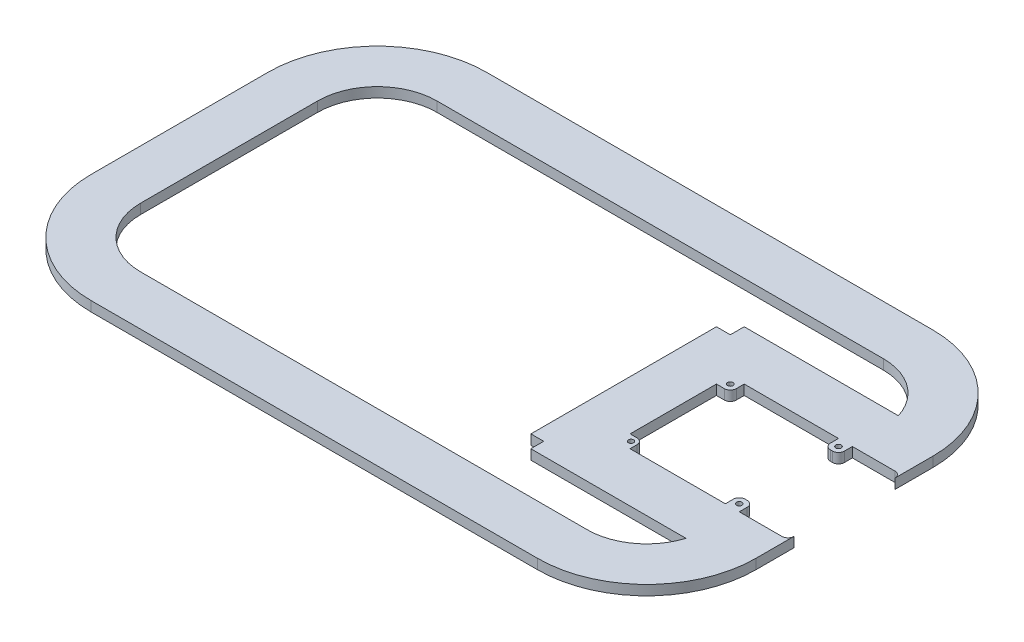
SolidWorks part; units mm, degrees
ref_plane "Front Plane" through (0, 0, 0) normal (0, 0, 1) x (1, 0, 0)
ref_plane "Top Plane" through (0, 0, 0) normal (0, 1, 0) x (1, 0, 0)
ref_plane "Right Plane" through (0, 0, 0) normal (1, 0, 0) x (0, 0, -1)
sketch "Sketch1" plane through (0, 0, 0) normal (0, 1, 0) x (1, 0, 0)
  line L0 (279.931, -90.3676) -> (279.931, -109.4976)
  line L1 (-0.099, 34.7624) -> (224.931, 34.7624)
  line L2 (-55.099, -20.2376) -> (-55.099, -109.4976)
  line L3 (-0.099, -164.4976) -> (224.931, -164.4976)
  line L4 (279.931, -20.2376) -> (279.931, -39.3676)
  line L5 (200.931, -36.3676) -> (248.431, -36.3676)
  line L6 (193.931, -43.3676) -> (193.931, -86.8676)
  line L7 (200.3979, -93.3676) -> (248.431, -93.3676)
  line L8 (253.5898, -118.3676) -> (253.5898, -118.3676)
  line L9 (-0.099, -139.4976) -> (224.931, -139.4976)
  line L10 (193.931, -86.8676) -> (197.3979, -86.8676)
  line L11 (200.3979, -89.8676) -> (200.3979, -93.3676)
  line L12 (200.931, -36.3676) -> (200.931, -40.3676)
  line L13 (197.931, -43.3676) -> (193.931, -43.3676)
  line L14 (-30.099, -20.2376) -> (-30.099, -109.4976)
  line L15 (-0.099, 9.7624) -> (224.931, 9.7624)
  line L16 (248.431, -36.3676) -> (248.431, -40.3676)
  line L17 (251.431, -43.3676) -> (252.431, -43.3676)
  line L18 (255.431, -40.3676) -> (255.431, -36.3676)
  line L19 (255.431, -36.3676) -> (276.931, -36.3676)
  line L20 (253.5898, -11.3676) -> (253.5898, -11.3676)
  line L21 (248.431, -93.3676) -> (248.431, -89.3676)
  line L22 (251.431, -86.3676) -> (252.431, -86.3676)
  line L23 (255.431, -89.3676) -> (255.431, -93.3676)
  line L24 (255.431, -93.3676) -> (276.931, -93.3676)
  line L25 (251.931, -11.3676) -> (253.5898, -11.3676)
  line L26 (251.931, -11.3676) -> (251.931, -11.3676)
  line L27 (251.931, -11.3676) -> (251.931, -11.3676)
  line L28 (251.931, -11.3676) -> (251.931, -11.3676)
  line L29 (175.931, -11.3676) -> (251.931, -11.3676)
  line L30 (175.931, -11.3676) -> (175.931, -18.3676)
  line L31 (175.931, -18.3676) -> (168.931, -18.3676)
  line L32 (168.931, -18.3676) -> (168.931, -111.8676)
  line L33 (168.931, -111.8676) -> (175.3979, -111.8676)
  line L34 (175.3979, -111.8676) -> (175.3979, -118.3676)
  line L35 (175.3979, -118.3676) -> (251.931, -118.3676)
  line L36 (251.931, -118.3676) -> (251.931, -118.3676)
  line L37 (251.931, -118.3676) -> (251.931, -118.3676)
  line L38 (251.931, -118.3676) -> (251.931, -118.3676)
  line L39 (251.931, -118.3676) -> (253.5898, -118.3676)
  arc A0 (-55.099, -109.4976) -> (-0.099, -164.4976) centre (-0.099, -109.4976) ccw
  arc A1 (224.931, -164.4976) -> (279.931, -109.4976) centre (224.931, -109.4976) ccw
  arc A2 (224.931, 34.7624) -> (279.931, -20.2376) centre (224.931, -20.2376) cw
  arc A3 (-0.099, 34.7624) -> (-55.099, -20.2376) centre (-0.099, -20.2376) ccw
  arc A4 (276.931, -36.3676) -> (279.931, -39.3676) centre (276.931, -39.3676) cw
  arc A5 (276.931, -93.3676) -> (279.931, -90.3676) centre (276.931, -90.3676) ccw
  arc A6 (197.3979, -86.8676) -> (200.3979, -89.8676) centre (197.3979, -89.8676) cw
  circle A7 centre (251.931, -39.8676) radius 1.375
  arc A8 (200.931, -40.3676) -> (197.931, -43.3676) centre (197.931, -40.3676) cw
  circle A9 centre (251.931, -89.8676) radius 1.375
  circle A10 centre (197.3979, -89.8676) radius 1.3186
  circle A11 centre (197.431, -39.8676) radius 1.375
  arc A12 (252.431, -43.3676) -> (255.431, -40.3676) centre (252.431, -40.3676) ccw
  arc A13 (248.431, -40.3676) -> (251.431, -43.3676) centre (251.431, -40.3676) ccw
  arc A14 (252.431, -86.3676) -> (255.431, -89.3676) centre (252.431, -89.3676) cw
  arc A15 (248.431, -89.3676) -> (251.431, -86.3676) centre (251.431, -89.3676) cw
  arc A16 (224.931, -139.4976) -> (253.5898, -118.3676) centre (224.931, -109.4976) ccw
  arc A17 (-30.099, -109.4976) -> (-0.099, -139.4976) centre (-0.099, -109.4976) ccw
  arc A18 (-0.099, 9.7624) -> (-30.099, -20.2376) centre (-0.099, -20.2376) ccw
  arc A19 (224.931, 9.7624) -> (253.5898, -11.3676) centre (224.931, -20.2376) cw
  arc A20 (253.5898, -11.3676) -> (253.5898, -11.3676) centre (253.5898, -11.3676) ccw
  arc A21 (251.931, -11.3676) -> (251.931, -11.3676) centre (251.931, -11.3676) ccw
  arc A22 (251.931, -11.3676) -> (251.931, -11.3676) centre (251.931, -11.3676) ccw
  arc A23 (175.931, -18.3676) -> (175.931, -18.3676) centre (175.931, -18.3676) cw
  arc A24 (175.3979, -111.8676) -> (175.3979, -111.8676) centre (175.3979, -111.8676) cw
  arc A25 (251.931, -118.3676) -> (251.931, -118.3676) centre (251.931, -118.3676) cw
  arc A26 (251.931, -118.3676) -> (251.931, -118.3676) centre (251.931, -118.3676) cw
  arc A27 (253.5898, -118.3676) -> (253.5898, -118.3676) centre (253.5898, -118.3676) cw
  dimension "D3" = 55
  dimension "D4" = 3
  dimension "D5" = 3
  dimension "D1" = 3
  dimension "D2" = 3
  dimension "D6" = 25
extrude "Boss-Extrude1" add sketch "Sketch1" along normal blind 5
